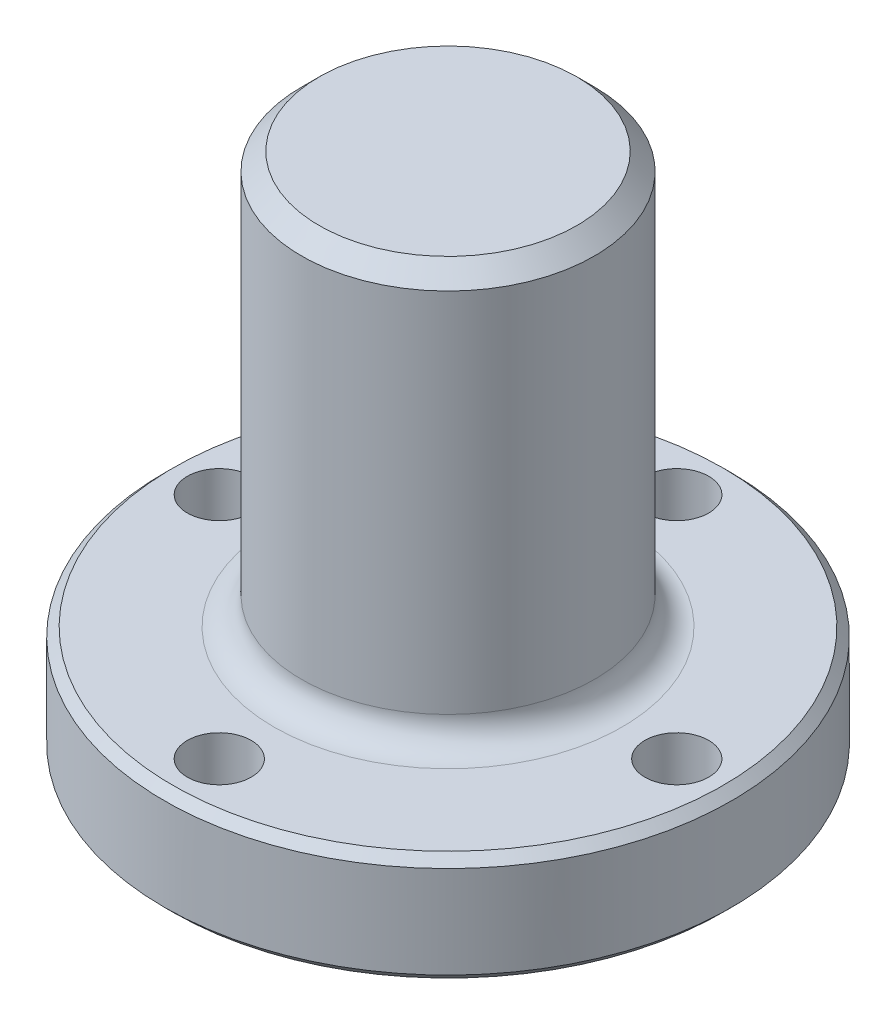
SolidWorks part; units mm, degrees
ref_plane "Front Plane" through (0, 0, 0) normal (1, 0, 0) x (0, 1, 0)
ref_plane "Top Plane" through (0, 0, 0) normal (0, 0, 1) x (0, 1, 0)
ref_plane "Right Plane" through (0, 0, 0) normal (0, 1, 0) x (-1, 0, 0)
sketch "Sketch1" plane through (0, 0, 0) normal (0, 0, 1) x (0, 1, 0)
  line L0 (-25.0317, 0) -> (-25.0317, 8.7122)
  line L1 (-25.0317, 8.7122) -> (-20.2057, 8.7122)
  line L2 (-20.2057, 8.7122) -> (-20.2057, 24.6126)
  line L3 (-20.2057, 24.6126) -> (-10.6807, 24.6126)
  line L4 (-10.6807, 24.6126) -> (-10.6807, 12.7)
  line L5 (-10.6807, 12.7) -> (25.0317, 12.7)
  line L6 (25.0317, 12.7) -> (25.0317, 0)
  line L7 (25.0317, 0) -> (-25.0317, 0)
  line L8 (-50.4317, 0) -> (50.4317, 0) construction
revolve "Revolve1" add sketch "Sketch1" angle 360 about L8
sketch "Sketch2" plane through (0, 0, 0) normal (0, 1, 0) x (-1, 0, 0)
  circle A0 centre (19.8374, 0) radius 2.7686
extrude "Cut-Extrude2" cut sketch "Sketch2" along normal blind 20.2057 from offset 20.2057
sketch "Sketch3" plane through (0, 0, 0) normal (0, 1, 0) x (-1, 0, 0)
  circle A0 centre (0, 19.8374) radius 2.7686
  circle A1 centre (-19.8374, 0) radius 2.7686
  circle A2 centre (0, -19.8374) radius 2.7686
extrude "Cut-Extrude4" cut sketch "Sketch3" along normal blind 20.2057 from offset 20.2057
fillet "Fillet1" radius 2.3876 1 edges at (0, -10.6807, -12.7)
chamfer "Chamfer1" distance 0.762 angle 45 2 edges at (0, -10.6807, -24.6126) (0, -20.2057, -24.6126)
chamfer "Chamfer2" distance 1.524 angle 45 1 edges at (0, 25.0317, -12.7)
